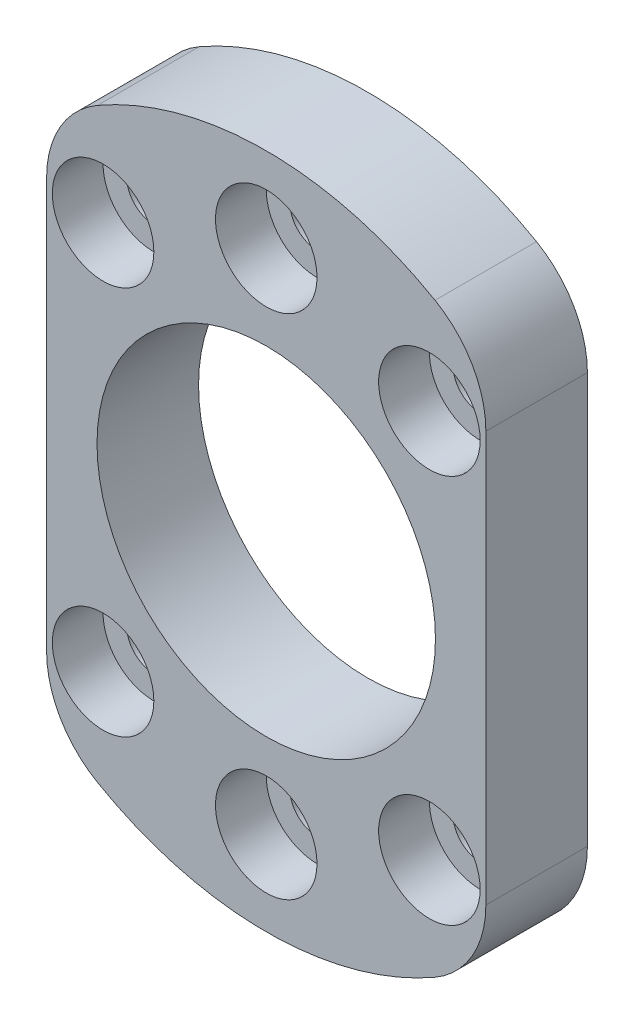
SolidWorks part; units mm, degrees
ref_plane "前视基准面" through (0, 0, 0) normal (0, 0, 1) x (1, 0, 0)
ref_plane "上视基准面" through (0, 0, 0) normal (0, 1, 0) x (1, 0, 0)
ref_plane "右视基准面" through (0, 0, 0) normal (1, 0, 0) x (0, 0, -1)
sketch "草图1" plane through (0, 0, 0) normal (0, 0, 1) x (1, 0, 0)
  line L0 (-12.98, 15.2026) -> (-12.98, -15.2026)
  line L2 (12.98, -15.2026) -> (12.98, 15.2026)
  arc A0 (-12.98, -15.2026) -> (12.98, -15.2026) centre (0, 0) ccw
  arc A1 (12.98, 15.2026) -> (-12.98, 15.2026) centre (0, 0) ccw
  circle A2 centre (0, 0) radius 10
  dimension "D1" = 39.98
  dimension "D3" = 20
  dimension "D2" = 12.98
  dimension "D4" = 12.98
extrude "拉伸1" add sketch "草图1" along normal blind 6
sketch "草图2" plane through (0, 0, 6) normal (0, 0, 1) x (1, 0, 0)
  line L0 (0, -1000) -> (0, 49000) construction
  line L1 (-642.7876, -766.0444) -> (31496.5929, 37536.1777) construction
  line L2 (642.7876, -766.0444) -> (-31496.5929, 37536.1777) construction
  circle A0 centre (0, 0) radius 15 construction
  circle A1 centre (-9.6418, 11.4907) radius 1.6
  circle A2 centre (0, 15) radius 1.6
  circle A3 centre (9.6418, 11.4907) radius 1.6
  circle A4 centre (-9.6418, -11.4907) radius 1.6
  circle A5 centre (0, -15) radius 1.6
  circle A6 centre (9.6418, -11.4907) radius 1.6
  dimension "D1" = 30
  dimension "D2" = 3.2
  dimension "D3" = 40
  dimension "D4" = 40
extrude "切除-拉伸1" cut sketch "草图2" against normal blind 7
fillet "圆角1" radius 6 1 edges at (-12.98, 15.2026, 3)
fillet "圆角2" radius 6 1 edges at (12.98, 15.2026, 3)
fillet "圆角3" radius 6 1 edges at (-12.98, -15.2026, 3)
fillet "圆角4" radius 6 1 edges at (12.98, -15.2026, 3)
sketch "草图3" plane through (0, 0, 6) normal (0, 0, 1) x (1, 0, 0)
  circle A0 centre (-9.6418, 11.4907) radius 3
  circle A1 centre (0, 15) radius 3
  circle A2 centre (9.6418, 11.4907) radius 3
  circle A3 centre (-9.6418, -11.4907) radius 3
  circle A4 centre (0, -15) radius 3
  circle A5 centre (9.6418, -11.4907) radius 3
  dimension "D1" = 6
extrude "切除-拉伸2" cut sketch "草图3" against normal blind 3
